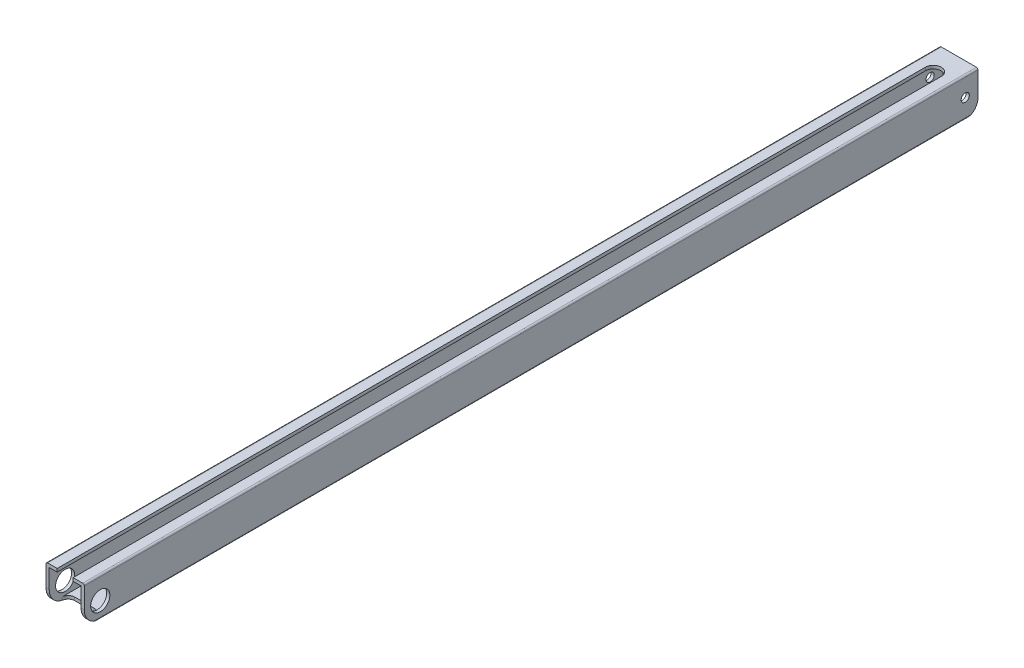
SolidWorks part; units mm, degrees
ref_plane "Front Plane" through (0, 0, 0) normal (0, 0, 1) x (1, 0, 0)
ref_plane "Top Plane" through (0, 0, 0) normal (0, 1, 0) x (1, 0, 0)
ref_plane "Right Plane" through (0, 0, 0) normal (1, 0, 0) x (0, 0, -1)
sketch "Sketch1" plane through (0, 0, 0) normal (0, 0, 1) x (1, 0, 0)
  line L1 (9.525, -9.525) -> (-9.525, -9.525) construction
  line L2 (9.525, -9.525) -> (9.525, 9.525) construction
  line L3 (9.525, 9.525) -> (-9.525, 9.525) construction
  line L4 (-9.525, -9.525) -> (-9.525, 9.525) construction
  line L5 (9.525, -9.525) -> (-9.525, 9.525) construction
  line L6 (9.525, 9.525) -> (-9.525, -9.525) construction
  line L7 (7.9375, -7.9375) -> (-7.9375, -7.9375) construction
  line L8 (7.9375, -7.9375) -> (7.9375, 7.9375) construction
  line L9 (7.9375, 7.9375) -> (-7.9375, 7.9375) construction
  line L10 (-7.9375, -7.9375) -> (-7.9375, 7.9375) construction
  line L11 (7.9375, -7.9375) -> (-7.9375, 7.9375) construction
  line L12 (7.9375, 7.9375) -> (-7.9375, -7.9375) construction
  point P0 (0, 0)
  point P6 (0, 0)
  dimension "Outside Height" = 19.05
  dimension "Wall Thickness" = 1.5875
  dimension "Outside Width" = 19.05
sketch "Sketch2" plane through (0, 0, 0) normal (1, 0, 0) x (0, 0, -1)
  line L0 (-222.25, 0) -> (222.25, 0) construction
  line L1 (0, 0) -> (0, 7.4072) construction
  point P0 (-199.39, 0)
  point P4 (0, 0)
  point P5 (199.39, 0)
  dimension "Length" = 444.5
  dimension "D1" = 22.86
sketch "Sketch3" plane through (0, 0, 0) normal (0, 0, 1) x (1, 0, 0)
  line L1 (-9.525, -9.525) -> (9.525, -9.525)
  line L2 (-9.525, -9.525) -> (-9.525, 9.525)
  line L3 (-9.525, 9.525) -> (9.525, 9.525)
  line L4 (9.525, -9.525) -> (9.525, 9.525)
  line L5 (-9.525, -9.525) -> (9.525, 9.525) construction
  line L6 (-9.525, 9.525) -> (9.525, -9.525) construction
  line L7 (7.9375, -7.9375) -> (-7.9375, -7.9375)
  line L8 (7.9375, -7.9375) -> (7.9375, 7.9375)
  line L9 (7.9375, 7.9375) -> (-7.9375, 7.9375)
  line L10 (-7.9375, -7.9375) -> (-7.9375, 7.9375)
  line L11 (7.9375, -7.9375) -> (-7.9375, 7.9375) construction
  line L12 (7.9375, 7.9375) -> (-7.9375, -7.9375) construction
  point P0 (0, 0)
  point P6 (0, 0)
  dimension "D1" = 19.05
  dimension "D2" = 19.05
  dimension "D3" = 1.5875
extrude "Boss-Extrude1" add sketch "Sketch3" along normal mid plane 444.5
fillet "Fillet1" radius 0.7937 4 edges at (-9.525, -9.525, 0) (-9.525, 9.525, 0) (9.525, -9.525, 0) (9.525, 9.525, 0)
sketch "Sketch4" plane through (0, 9.525, 0) normal (0, 1, 0) x (1, 0, 0)
  line L0 (-3.9688, 209.55) -> (-3.9687, -222.25)
  line L1 (8.7312, -222.25) -> (-8.7312, -222.25) construction
  line L2 (-3.9687, -222.25) -> (3.9687, -222.25)
  line L3 (3.9687, -222.25) -> (3.9688, 209.55)
  line L4 (8.7312, 222.25) -> (-8.7312, 222.25) construction
  arc A0 (-3.9688, 209.55) -> (3.9688, 209.55) centre (0, 209.55) cw
  point P9 (0, 0)
  dimension "D1" = 12.7
  dimension "D2" = 7.9375
extrude "Cut-Extrude1" cut sketch "Sketch4" against normal up to next
sketch "Sketch5" plane through (0, -9.525, 0) normal (0, -1, 0) x (-1, 0, 0)
  line L0 (7.9375, -222.25) -> (7.9375, -212.725)
  line L1 (-7.9375, -222.25) -> (-7.9375, -212.725)
  line L2 (-7.9375, -212.725) -> (7.9375, -212.725)
  line L3 (7.9375, -222.25) -> (-7.9375, -222.25)
  dimension "D1" = 9.525
extrude "Cut-Extrude2" cut sketch "Sketch5" against normal up to next
fillet "Fillet2" radius 3.175 2 edges at (7.9375, -8.7312, 212.725) (-7.9375, -8.7312, 212.725)
sketch "Sketch6" plane through (9.525, 0, 0) normal (1, 0, 0) x (0, 0, -1)
  line L0 (-222.25, -8.7312) -> (-222.25, 8.7312) construction
  line L1 (222.25, -9.525) -> (-222.25, -9.525) construction
  line L2 (-222.25, -1.5875) -> (-222.25, -9.525)
  line L3 (-222.25, -9.525) -> (-214.3125, -9.525)
  arc A0 (-222.25, -1.5875) -> (-214.3125, -9.525) centre (-214.3125, -1.5875) ccw
  dimension "D1" = 7.9375
extrude "Cut-Extrude3" cut sketch "Sketch6" against normal through all
sketch "Sketch7" plane through (9.525, 0, 0) normal (1, 0, 0) x (0, 0, -1)
  line L0 (222.25, -8.7312) -> (222.25, 8.7312) construction
  circle A0 centre (-214.3125, -1.5875) radius 4.7625
  circle A1 centre (215.9, 0) radius 2.032
  point P7 (0, 0)
  point P9 (207.6124, 7.4902)
  dimension "D1" = 9.525
  dimension "D2" = 4.064
  dimension "D3" = 6.35
extrude "Cut-Extrude4" cut sketch "Sketch7" against normal through all
sketch "Sketch8" plane through (9.525, 0, 0) normal (1, 0, 0) x (0, 0, -1)
  line L0 (222.25, -9.525) -> (-214.3125, -9.525) construction
  line L1 (222.25, -8.7312) -> (222.25, 8.7312) construction
  line L2 (215.9, -9.525) -> (222.25, -9.525)
  line L3 (222.25, -9.525) -> (222.25, -3.175)
  arc A0 (215.9, -9.525) -> (222.25, -3.175) centre (215.9, -3.175) ccw
  dimension "D1" = 6.35
extrude "Cut-Extrude5" cut sketch "Sketch8" against normal through all
equation "\"D1@Sketch3\"=\"Outside Width@Sketch1\""
equation "\"D2@Sketch3\"=\"Outside Height@Sketch1\""
equation "\"D3@Sketch3\"=\"Wall Thickness@Sketch1\""
equation "\"D1@Boss-Extrude1\"=\"Length@Sketch2\""
equation "\"D1@Fillet1\"=\"Wall Thickness@Sketch1\"*.5"
equation "\"D1@Sketch2\"=\"Outside Width@Sketch1\"*1.2"
